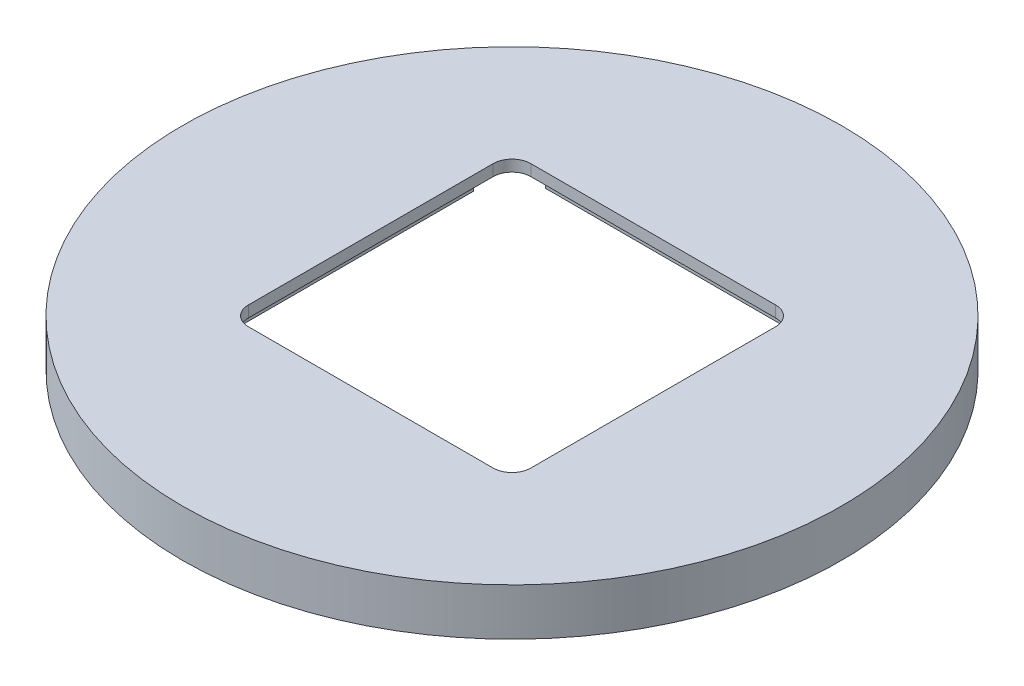
SolidWorks part; units mm, degrees
material "ABS"
ref_plane "Front Plane" through (0, 0, 0) normal (0, 0, 1) x (1, 0, 0)
ref_plane "Top Plane" through (0, 0, 0) normal (0, 1, 0) x (1, 0, 0)
ref_plane "Right Plane" through (0, 0, 0) normal (1, 0, 0) x (0, 0, -1)
sketch "Sketch2" plane through (0, 0, 0) normal (0, 1, 0) x (1, 0, 0)
  line L1 (-12.1337, 8.6287) -> (-30.6337, 8.6287)
  line L2 (-12.1337, 8.6287) -> (-12.1337, -9.8713)
  line L3 (-12.1337, -9.8713) -> (-30.6337, -9.8713)
  line L4 (-30.6337, 8.6287) -> (-30.6337, -9.8713)
  line L5 (-12.1337, 8.6287) -> (-30.6337, -9.8713) construction
  line L6 (-12.1337, -9.8713) -> (-30.6337, 8.6287) construction
  circle A0 centre (-21.3837, -0.6213) radius 17.5
  dimension "D1" = 18.5
  dimension "D2" = 35
  dimension "D3" = 21.3837
  dimension "D4" = 18.5
extrude "Boss-Extrude1" add sketch "Sketch2" along normal blind 2.5
sketch "Sketch4" plane through (0, 0, 0) normal (0, -1, 0) x (1, 0, 0)
  circle A0 centre (-21.5697, 15.5896) radius 1.67
  dimension "D1" = 3.34
extrude "Cut-Extrude1" cut sketch "Sketch4" against normal blind 1.15
pattern_circular "CirPattern1" count 4 over 360 about axis through (-21.3837, 0, 0.6213) along (0, 1, 0) of "Cut-Extrude1"
sketch "Sketch5" plane through (0, 2.5, 0) normal (0, 1, 0) x (1, 0, 0)
  line L1 (-13.8837, 6.8787) -> (-28.8837, 6.8787)
  line L2 (-13.8837, 6.8787) -> (-13.8837, -8.1213)
  line L3 (-13.8837, -8.1213) -> (-28.8837, -8.1213)
  line L4 (-28.8837, 6.8787) -> (-28.8837, -8.1213)
  line L5 (-13.8837, 6.8787) -> (-28.8837, -8.1213) construction
  line L6 (-13.8837, -8.1213) -> (-28.8837, 6.8787) construction
  point P0 (-21.3837, -0.6213)
  line M1 (-30.6337, -9.8713) -> (-30.6337, 8.6287)
  line M2 (-30.6337, 8.6287) -> (-12.1337, 8.6287)
  line M3 (-12.1337, 8.6287) -> (-12.1337, -9.8713)
  line M4 (-12.1337, -9.8713) -> (-30.6337, -9.8713)
  dimension "D1" = 15
  dimension "D2" = 15
extrude "Boss-Extrude2" add sketch "Sketch5" against normal blind 0.6 contours L4 L1 L2 L3 M1 M4 M3 M2
fillet "Fillet1" radius 1 4 edges at (-28.8837, 2.2, 8.1213) (-13.8837, 2.2, 8.1213) (-13.8837, 2.2, -6.8787) (-28.8837, 2.2, -6.8787)
sketch "Sketch6" plane through (0, 0, 0) normal (0, -1, 0) x (-1, 0, 0)
  line L0 (30.6337, -9.8713) -> (30.1337, -9.3713) construction
  line L1 (30.6337, -9.8713) -> (30.1337, -9.8713) construction
  line L2 (12.1337, -9.8713) -> (30.6337, -9.8713) construction
  line L3 (30.1337, -9.8713) -> (30.1337, -9.3713) construction
  line L4 (12.2337, -9.7713) -> (12.7337, -9.2713) construction
  line L5 (12.2337, -9.7713) -> (12.2337, -9.2713) construction
  line L6 (12.2337, -9.2713) -> (12.7337, -9.2713) construction
  line L7 (12.3337, 8.6287) -> (12.8337, 8.1287) construction
  line L8 (12.3337, 8.6287) -> (12.8337, 8.6287) construction
  line L9 (12.8337, 8.6287) -> (12.8337, 8.1287) construction
  line L10 (30.7337, 8.5287) -> (30.2337, 8.0287) construction
  line L11 (30.7337, 8.5287) -> (30.7337, 8.0287) construction
  line L12 (30.7337, 8.0287) -> (30.2337, 8.0287) construction
  circle A0 centre (30.1337, -9.3713) radius 1.5
  circle A1 centre (12.7337, -9.2713) radius 1.5
  circle A2 centre (12.8337, 8.1287) radius 1.5
  circle A3 centre (30.2337, 8.0287) radius 1.5
  point P22 (21.4837, -0.6213)
  dimension "D3" = 3
  dimension "D1" = 0.5
  dimension "D2" = 0.5
  dimension "D4" = 4
extrude "Cut-Extrude2" cut sketch "Sketch6" against normal up to surface (1.9 mm away) up to face at (-21.3837, 1.9, 0.6213)
